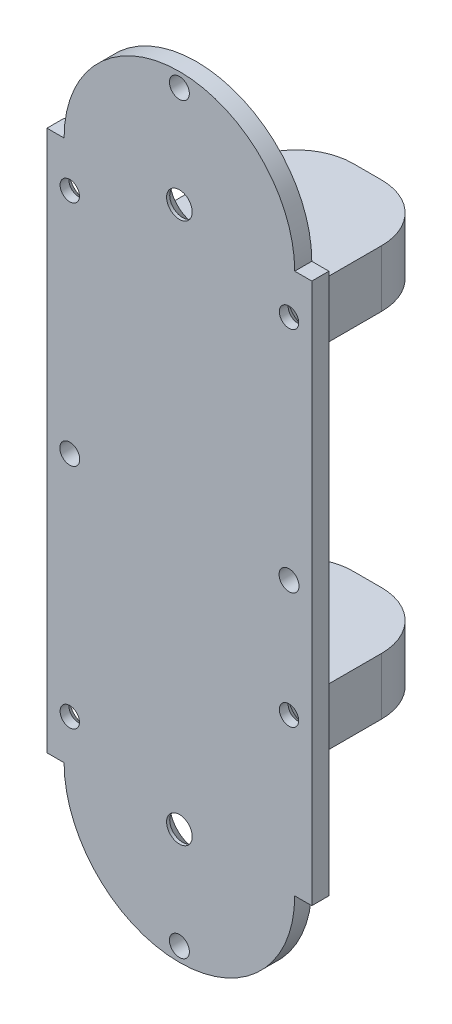
SolidWorks part; units mm, degrees
ref_plane "Front Plane" through (0, 0, 0) normal (0, 0, 1) x (1, 0, 0)
ref_plane "Top Plane" through (0, 0, 0) normal (0, 1, 0) x (1, 0, 0)
ref_plane "Right Plane" through (0, 0, 0) normal (1, 0, 0) x (0, 0, -1)
sketch "Schizzo1" plane through (0, 0, 0) normal (0, 0, 1) x (1, 0, 0)
  line L18 (0, -47.5) -> (0, 47.5) construction
  line L19 (-20.25, -47.5) -> (-20.25, 47.5) construction
  line L20 (20.25, -47.5) -> (20.25, 47.5) construction
  line L21 (20.25, -47.5) -> (23.25, -47.5)
  line L22 (23.25, -47.5) -> (-23.25, -47.5) construction
  line L23 (23.25, -47.5) -> (23.25, 47.5) construction
  line L24 (23.25, 47.5) -> (-23.25, 47.5) construction
  line L25 (-23.25, -47.5) -> (-23.25, 47.5) construction
  line L26 (23.25, -47.5) -> (-23.25, 47.5) construction
  line L27 (23.25, 47.5) -> (-23.25, -47.5) construction
  line L28 (23.25, -47.5) -> (23.25, 47.5)
  line L29 (23.25, 47.5) -> (20.25, 47.5)
  line L30 (-20.25, 47.5) -> (-23.25, 47.5)
  line L31 (-23.25, 47.5) -> (-23.25, -47.5)
  line L32 (-23.25, -47.5) -> (-20.25, -47.5)
  arc A14 (-20.25, -47.5) -> (20.25, -47.5) centre (0, -47.5) ccw construction
  arc A15 (20.25, 47.5) -> (-20.25, 47.5) centre (0, 47.5) ccw construction
  arc A16 (-20.25, 47.5) -> (20.25, 47.5) centre (0, 47.5) cw
  arc A17 (-20.25, -47.5) -> (20.25, -47.5) centre (0, -47.5) ccw
  point P2 (0, 0)
  point P8 (0, 0)
  dimension "D3" = 46.5
  dimension "D2" = 95
  dimension "D1" = 20.25
  dimension "D4" = 95
extrude "Estrusione-Estrusione1" add sketch "Schizzo1" along normal blind 3
hole_wizard "Foro svasato per Vite M4-1" positions "Schizzo4" profile "Schizzo5" countersink size "M4" standard "ISO" end condition up to next
sketch "Schizzo4" plane through (0, 0, 0) normal (0, 0, 1) x (1, 0, 0)
  point P0 (0, 47.5)
  point P3 (0, -47.5)
sketch "Schizzo5" plane through (0, 47.5, 0) normal (1, 0, 0) x (0, 1, 0)
  line L0 (0, 0) -> (0, 3)
  line L1 (0, 3) -> (2.25, 3)
  line L2 (2.25, 3) -> (2.25, 2.45)
  line L3 (2.25, 2.45) -> (4.7, 0)
  line L5 (4.7, 0) -> (0, 0)
  line L6 (-2.25, 2.45) -> (-4.7, 0) construction
  line L11 (0, -6.35) -> (0, 107.95) construction
  dimension "Thru Hole Dia." = 4.5
  dimension "Thru Hole Depth" = 3
  dimension "Near C'Sink Dia." = 9.4
  dimension "Near C'Sink Angle" = 90
hole_wizard "Foro svasato per Vite M3-1" positions "Schizzo7" profile "Schizzo8" countersink size "M3" standard "ISO" end condition up to next
sketch "Schizzo7" plane through (0, 0, 0) normal (0, 0, -1) x (-1, 0, 0)
  line L1 (23.25, 47.5) -> (23.25, -47.5) construction
  line L2 (20.25, 47.5) -> (23.25, 47.5) construction
  line L3 (23.25, -47.5) -> (20.25, -47.5) construction
  line L5 (-23.25, 47.5) -> (-20.25, 47.5) construction
  line L6 (-23.25, -47.5) -> (-23.25, 47.5) construction
  line L7 (-20.25, -47.5) -> (-23.25, -47.5) construction
  point P0 (-19.25, 40)
  point P2 (-19.25, -20.5)
  point P4 (19.25, -40)
  point P6 (19.25, 40)
  dimension "D1" = 4
  dimension "D2" = 7.5
  dimension "D3" = 7.5
  dimension "D4" = 7.5
  dimension "D5" = 4
  dimension "D6" = 27
sketch "Schizzo8" plane through (19.25, 40, 0) normal (1, 0, 0) x (0, 1, 0)
  line L0 (0, 0) -> (0, 3)
  line L1 (0, 3) -> (1.7, 3)
  line L2 (1.7, 3) -> (1.7, 1.45)
  line L3 (1.7, 1.45) -> (3.15, 0)
  line L5 (3.15, 0) -> (0, 0)
  line L6 (-1.7, 1.45) -> (-3.15, 0) construction
  line L11 (0, -6.35) -> (0, 107.95) construction
  dimension "Thru Hole Dia." = 3.4
  dimension "Thru Hole Depth" = 3
  dimension "Near C'Sink Dia." = 6.3
  dimension "Near C'Sink Angle" = 90
sketch "Schizzo9" plane through (0, 0, 0) normal (0, 0, -1) x (-1, 0, 0)
  line L0 (0, -26.1442) -> (0, 0) construction
  line L1 (0, 0) -> (11.4053, 0) construction
  circle A0 centre (-19.25, 0) radius 1.75
  circle A1 centre (19.25, 0) radius 1.75
  circle A2 centre (0, 65.25) radius 1.75
  circle A3 centre (0, -65.25) radius 1.75
  dimension "D3" = 3.5
  dimension "D1" = 130.5
  dimension "D2" = 38.5
extrude "Taglio-Estrusione2" cut sketch "Schizzo9" against normal up to next
ref_plane "Plane1" through (0, 0, 0) normal (0, 0, -1) x (-1, 0, 0)
sketch "Sketch4" plane through (0, 0, 0) normal (0, 0, -1) x (-1, 0, 0)
  line L0 (12.5, 36) -> (-12.5, 36)
  line L1 (12.5, 36) -> (12.5, 26)
  line L2 (-12.5, 36) -> (-12.5, 26)
  line L3 (12.5, 26) -> (-12.5, 26)
  line L4 (-12.5, -26) -> (-12.5, -36)
  line L5 (-12.5, -26) -> (12.5, -26)
  line L6 (-12.5, -36) -> (12.5, -36)
  line L7 (12.5, -26) -> (12.5, -36)
  line L8 (0, 67.75) -> (0, -67.75) construction
  line L9 (23.25, 0) -> (-23.25, 0) construction
  line L10 (23.25, 47.5) -> (23.25, -47.5) construction
  line L11 (-23.25, -47.5) -> (-23.25, 47.5) construction
  arc A0 (20.25, 47.5) -> (-20.25, 47.5) centre (0, 47.5) ccw construction
  arc A1 (-20.25, -47.5) -> (20.25, -47.5) centre (0, -47.5) ccw construction
  dimension "D1" = 10
  dimension "D2" = 25
  dimension "D3" = 12.5
  dimension "D4" = 26
  dimension "D5" = 26
  dimension "D6" = 10
  dimension "D7" = 25
extrude "Boss-Extrude3" add sketch "Sketch4" along normal blind 30
ref_plane "Plane2" through (0, 36, 0) normal (0, 1, 0) x (1, 0, 0)
sketch "Sketch6" plane through (0, 36, 0) normal (0, 1, 0) x (1, 0, 0)
  line L0 (-12.5, 15) -> (12.5, 15) construction
  line L1 (-12.5, 30) -> (-12.5, 0) construction
  line L2 (12.5, 30) -> (12.5, 0) construction
  line L3 (0, 30) -> (0, 0) construction
  line L4 (-12.5, 30) -> (12.5, 30) construction
  line L5 (-12.5, 0) -> (12.5, 0) construction
  circle A0 centre (0, 15) radius 3
  dimension "D1" = 6
extrude "Cut-Extrude2" cut sketch "Sketch6" against normal through all
chamfer "Chamfer1" distance 2 angle 45 8 edges at (12.5, -31, 0) (0, -36, 0) (-12.5, -31, 0) (0, -26, 0) (0, 36, 0) (12.5, 31, 0) (0, 26, 0) (-12.5, 31, 0)
fillet "Fillet1" radius 10 4 edges at (-12.5, -31, -30) (12.5, -31, -30) (-12.5, 31, -30) (12.5, 31, -30)
